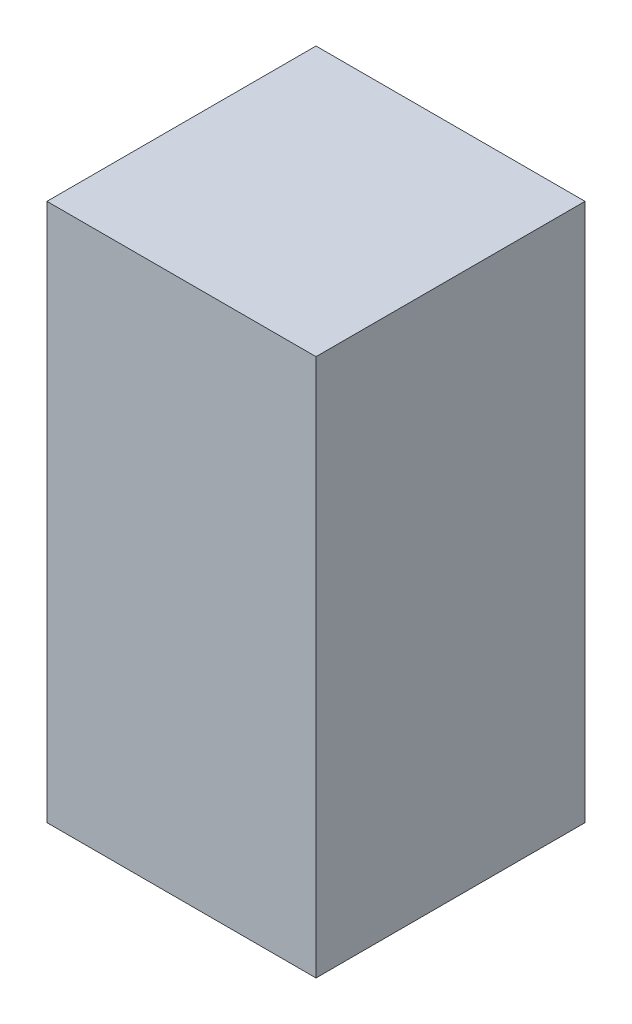
SolidWorks part; units mm, degrees
ref_plane "Front Plane" through (0, 0, 0) normal (0, 0, 1) x (1, 0, 0)
ref_plane "Top Plane" through (0, 0, 0) normal (0, 1, 0) x (1, 0, 0)
ref_plane "Right Plane" through (0, 0, 0) normal (1, 0, 0) x (0, 0, -1)
sketch "Sketch1" plane through (0, 0, 0) normal (0, 1, 0) x (1, 0, 0)
  line L1 (-50, -50) -> (50, -50)
  line L2 (-50, -50) -> (-50, 50)
  line L3 (-50, 50) -> (50, 50)
  line L4 (50, -50) -> (50, 50)
  line L5 (-50, -50) -> (50, 50) construction
  line L6 (-50, 50) -> (50, -50) construction
  point P0 (0, 0)
  dimension "D1" = 100
  dimension "D2" = 100
extrude "Boss-Extrude1" add sketch "Sketch1" along normal blind 200
